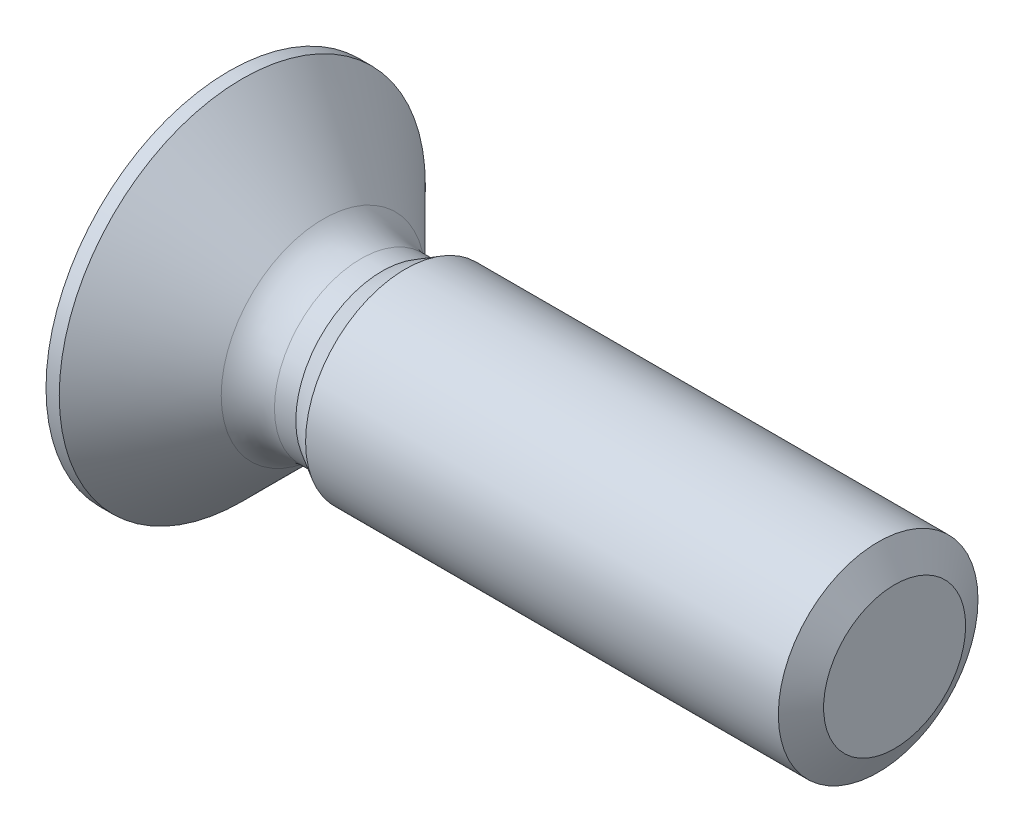
SolidWorks part; units mm, degrees
revolve "基体-旋转" add sketch "草图1" angle 360 about L0
sketch "草图1" plane through (0, 0, 0) normal (0, 0, 1) x (1, 0, 0)
  line L0 (0, 0) -> (4.4175, 0) construction
  line L1 (0, 0) -> (0, 2.75)
  line L2 (0, 2.75) -> (0.199, 2.75)
  line L3 (0.199, 2.75) -> (1.4157, 1.5333)
  line L4 (1.9814, 1.299) -> (2.3019, 1.299)
  line L5 (2.3019, 1.299) -> (2.65, 1.5)
  line L6 (2.65, 1.5) -> (10, 1.5)
  line L7 (10, 1.5) -> (10, 0)
  line L8 (0, 0) -> (10, 0)
  arc A0 (1.9814, 1.299) -> (1.4157, 1.5333) centre (1.9814, 2.099) cw
  point P12 (1.65, 1.299)
  dimension "D2" = 0.8
  dimension "D1" = 2.598
  dimension "d" = 3
  dimension "dk" = 5.5
  dimension "k" = 1.65
  dimension "D5" = 45
  dimension "a" = 1
  dimension "l" = 10
  dimension "D8" = 30
cosmetic thread "装饰螺纹线2" parameters "D1"=7.35, "D2"=2.5
ref_plane "前视" through (0, 0, 0) normal (0, 0, 1) x (1, 0, 0)
ref_plane "上视" through (0, 0, 0) normal (0, 1, 0) x (1, 0, 0)
ref_plane "右视" through (0, 0, 0) normal (1, 0, 0) x (0, 0, -1)
sketch "尺寸草图" plane through (0, 0, 0) normal (0, 0, 1) x (1, 0, 0)
  line L0 (0, 0) -> (10, 0)
  point P3 (1.65, 0)
  point P4 (1, 0)
  point P5 (3, 0)
  point P6 (5.5, 0)
  point P7 (6.8, 0)
  point P8 (3.5943, 0)
  point P9 (9.2, 0)
  point P10 (7.9, 0)
  point P11 (9.5, 0)
  dimension "d" = 3
  dimension "dk" = 5.5
  dimension "k" = 1.65
  dimension "a" = 1
  dimension "l" = 10
  dimension "r" = 0.8
  dimension "m" = 3.2
  dimension "h" = 2.1
  dimension "p" = 0.5
sketch "草图2" plane through (0, 0, 0) normal (0, 0, 1) x (1, 0, 0)
  line L0 (9.7527, 1.5) -> (10.2527, 1.5)
  line L1 (10.2527, 1.5) -> (10, 1.067)
  line L2 (10, 1.067) -> (9.7527, 1.5)
  line L3 (10, -1.5) -> (10, 1.5) construction
  line L6 (0, 0) -> (-0.4315, 0) construction
  dimension "D1" = 0.5
  dimension "D2" = 0.433
  dimension "D3" = 1.5
  dimension "D4" = 60
revolve "切除-旋转1" cut sketch "草图2" angle 360 about L6
pattern_linear "阵列(线性)1" [suppressed] count 15 spacing 0.5 along (1, 0, 0)
sketch "草图3" plane through (0, 0, 0) normal (-1, 0, 0) x (0, 0, 1)
  line L0 (0, 0) -> (1.6329, 0) construction
  line L1 (0, 0) -> (0, 0.8499) construction
  line L2 (-1.6, 0.25) -> (1.6, 0.25)
  line L3 (-1.6, 0.25) -> (-1.6, -0.25)
  line L4 (-1.6, -0.25) -> (1.6, -0.25)
  line L5 (1.6, 0.25) -> (1.6, -0.25)
  dimension "m" = 3.2
  dimension "D1" = 0.5
ref_plane "基准面1" through (2.1, 0, 0) normal (-1, 0, 0) x (0, 0, 1)
sketch "草图4" plane through (2.1, 0, 0) normal (-1, 0, 0) x (0, 0, 1)
  point P0 (0, 0)
loft "切除-放样1" cut profiles "草图3", "草图4"
pattern_circular "阵列(圆周)1" count 2 every 90 about axis through (0, 0, 0) along (1, 0, 0) of "切除-放样1"
equation "\"l@草图1\" = \"l@尺寸草图\""
equation "\"k@草图1\" = \"k@尺寸草图\""
equation "\"a@草图1\" = \"a@尺寸草图\""
equation "\"d@草图1\" = \"d@尺寸草图\""
equation "\"dk@草图1\" = \"dk@尺寸草图\""
equation "\"D2@草图1\" = \"r@尺寸草图\""
equation "\"m@草图3\" = \"m@尺寸草图\""
equation "\"h@基准面1\" = \"h@尺寸草图\""
equation "\"D3@阵列(线性)1\" = \"p@尺寸草图\""
equation "\"D3@草图2\" = \"d@草图1\" / 2"
equation "\"D1@装饰螺纹线2\" = \"l@草图1\" - \"k@草图1\" - \"a@草图1\""
equation "\"D2@装饰螺纹线2\" = \"d@尺寸草图\"- \"p@尺寸草图\""
equation "\"D1@阵列(线性)1\" = (  \"l@草图1\" - \"k@草图1\" - \"a@草图1\" )  / \"p@尺寸草图\""
equation "\"D1@草图3\" = \"p@尺寸草图\""
equation "\"D1@草图1\" = \"d@尺寸草图\"*0.866"
equation "\"D2@草图2\" = \"p@尺寸草图\"*0.866"
equation "\"D1@草图2\" = \"p@尺寸草图\""
